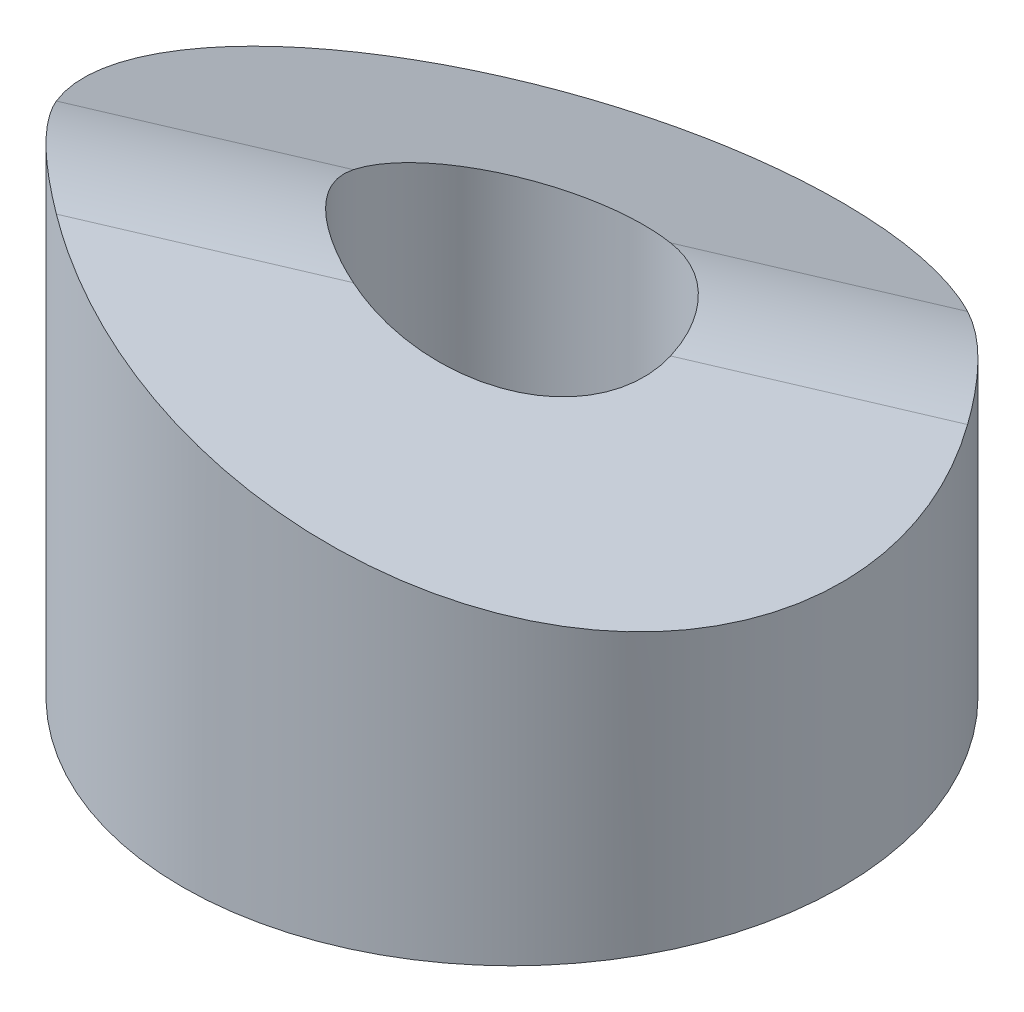
SolidWorks part; units mm, degrees
ref_plane "Front Plane" through (0, 0, 0) normal (0, 0, 1) x (1, 0, 0)
ref_plane "Top Plane" through (0, 0, 0) normal (0, 1, 0) x (1, 0, 0)
ref_plane "Right Plane" through (0, 0, 0) normal (1, 0, 0) x (0, 0, -1)
sketch "Sketch1" plane through (0, 0, 0) normal (0, 1, 0) x (1, 0, 0)
  circle A0 centre (0, 0) radius 3.175
  circle A1 centre (0, 0) radius 7.9375
  dimension "D1" = 6.35
  dimension "D2" = 4.7625
extrude "Boss-Extrude1" add sketch "Sketch1" along normal blind 12.7
sketch "Sketch2" plane through (0, 0, 0) normal (1, 0, 0) x (0, 0, -1)
  line L0 (7.9375, 12.7) -> (-7.9375, 12.7) construction
  line L1 (7.9375, 12.7) -> (-7.9375, 12.7)
  line L2 (-7.9375, 12.7) -> (7.9375, 6.35)
  line L3 (7.9375, 0) -> (7.9375, 12.7) construction
  line L4 (7.9375, 6.35) -> (7.9375, 12.7)
  dimension "D1" = 6.35
extrude "Cut-Extrude1" cut sketch "Sketch2" against normal through all both and the other way through all
sketch "Sketch3" plane through (0, 0, 0) normal (0, 0, 1) x (1, 0, 0)
  line L0 (-7.9375, 0) -> (7.9375, 0) construction
  line L1 (-7.9375, 0) -> (7.9375, 0)
  line L2 (-7.9375, 0) -> (-7.9375, 12.7)
  line L3 (-7.9375, 12.7) -> (7.9375, 12.7)
  line L4 (7.9375, 12.7) -> (7.9375, 0)
  line L5 (-7.9375, 12.7) -> (7.9375, 6.35)
  dimension "D1" = 12.7
  dimension "D2" = 6.35
extrude "Cut-Extrude3" cut sketch "Sketch3" against normal through all both and the other way through all contours L3 L5 L4
fillet "Fillet1" radius 6.35 2 edges at (-3.9289, 11.0965, 3.9289) (3.9289, 7.9535, -3.9289)
